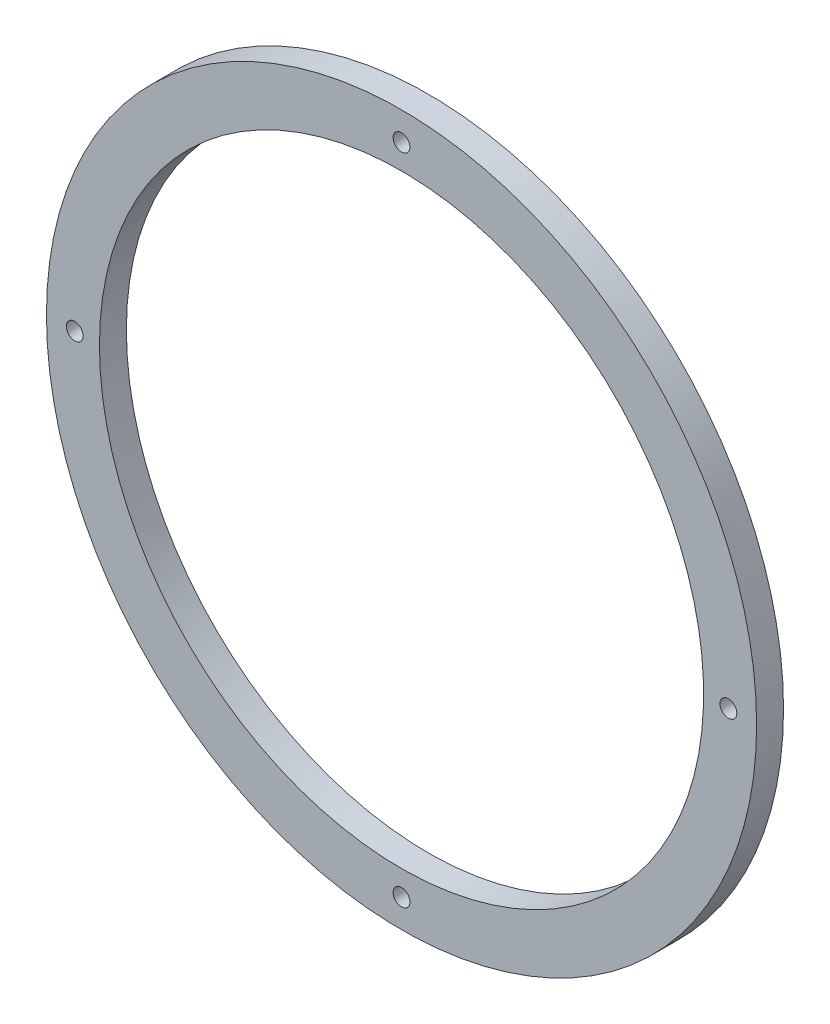
SolidWorks part; units mm, degrees
material "6061 Alloy"
ref_plane "Front Plane" through (0, 0, 0) normal (0, 0, 1) x (1, 0, 0)
ref_plane "Top Plane" through (0, 0, 0) normal (0, 1, 0) x (1, 0, 0)
ref_plane "Right Plane" through (0, 0, 0) normal (1, 0, 0) x (0, 0, -1)
sketch "Sketch1" plane through (0, 0, 0) normal (0, 0, 1) x (1, 0, 0)
  line L0 (0, 92.5) -> (0, 0) construction
  line L1 (0, 0) -> (-92.5, 0) construction
  line L2 (-92.5, 0) -> (0, 92.5) construction
  circle A0 centre (0, 0) radius 100.5
  circle A1 centre (0, 0) radius 85.5
  circle A2 centre (0, 92.5) radius 2.3812
  circle A3 centre (92.5, 0) radius 2.3813
  circle A4 centre (0, -92.5) radius 2.3812
  circle A5 centre (-92.5, 0) radius 2.3813
  point P16 (0, 0)
  dimension "D1" = 171
  dimension "D4" = 4.7625
  dimension "D3" = 92.5
  dimension "D2" = 15
  dimension "D5" = 4
extrude "Boss-Extrude1" add sketch "Sketch1" along normal blind 7.62
